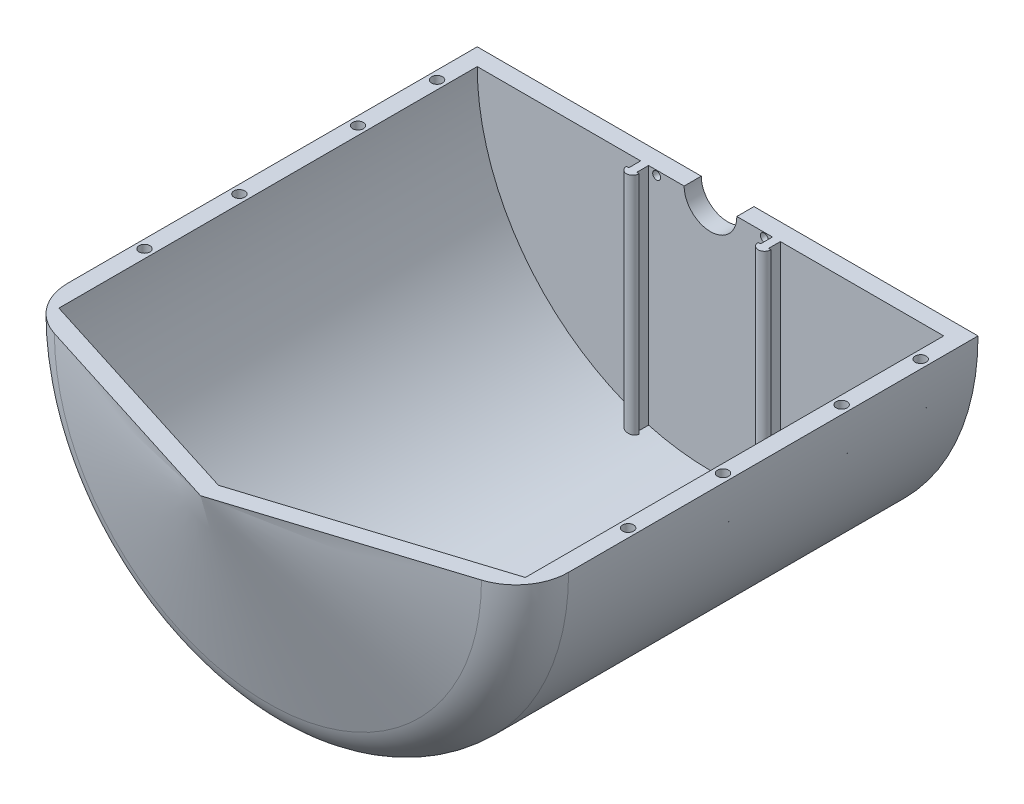
SolidWorks part; units mm, degrees
material "PVC 0.007 Plasticized"
ref_plane "Front Plane" through (0, 0, 0) normal (0, 0, 1) x (1, 0, 0)
ref_plane "Top Plane" through (0, 0, 0) normal (0, 1, 0) x (1, 0, 0)
ref_plane "Right Plane" through (0, 0, 0) normal (1, 0, 0) x (0, 0, -1)
sketch "Sketch1" plane through (0, 0, 0) normal (0, 1, 0) x (1, 0, 0)
  line L0 (0, 75) -> (95, 75)
  line L1 (95, 75) -> (95, -95)
  line L2 (95, -95) -> (0, -125)
  line L3 (0, -125) -> (0, 75) construction
  line L4 (0, 75) -> (0, -125)
  dimension "D1" = 200
  dimension "D2" = 170
  dimension "D3" = 95
  dimension "D4" = 75
  dimension "D5" = 95
revolve "Revolve1" add sketch "Sketch1" angle 180 about L3
sketch "Sketch2" plane through (0, 0, 0) normal (0, 1, 0) x (1, 0, 0)
  line L5 (0, 68.5) -> (0, -118.1836) construction
  line L6 (0, 68.5) -> (0, -118.1836)
  line L10 (-88.5, -90.2362) -> (0, -118.1836)
  line L11 (0, -118.1836) -> (88.5, -90.2362)
  line L12 (88.5, -90.2362) -> (88.5, 68.5)
  line L13 (88.5, 68.5) -> (-88.5, 68.5)
  line L14 (-88.5, 68.5) -> (-88.5, -90.2362)
  line L16 (0, -118.1836) -> (88.5, -90.2362)
  line L17 (88.5, -90.2362) -> (88.5, 68.5)
  line L18 (88.5, 68.5) -> (0, 68.5)
  dimension "D1" = 6.5
revolve "Cut-Revolve3" cut sketch "Sketch2" angle 360 about L5
sketch "Sketch3" plane through (0, 0, 0) normal (0, 1, 0) x (1, 0, 0)
  line L0 (-88.5, 68.5) -> (-95, 68.5) construction
  line L1 (-95, -95) -> (-95, 75) construction
  line L2 (-91.75, 68.5) -> (-91.75, -96.0263) construction
  line L3 (0, -125) -> (-95, -95) construction
  line L4 (0, 68.5) -> (0, -90.2362) construction
  line L5 (-88.5, 68.5) -> (88.5, 68.5) construction
  line L6 (88.5, -90.2362) -> (-88.5, -90.2362) construction
  circle A1 centre (-91.75, 56.5) radius 2.075
  circle A2 centre (-91.75, 26.5) radius 2.075
  circle A3 centre (-91.75, -18.5) radius 2.075
  circle A4 centre (-91.75, -54.5) radius 2.075
  circle A5 centre (91.75, -54.5) radius 2.075
  circle A6 centre (91.75, -18.5) radius 2.075
  circle A7 centre (91.75, 26.5) radius 2.075
  circle A8 centre (91.75, 56.5) radius 2.075
  dimension "D1" = 4.15
  dimension "D2" = 30
  dimension "D3" = 45
  dimension "D4" = 36
  dimension "D5" = 12
sketch "Sketch4" plane through (0, 0, 0) normal (0, 0, 1) x (1, 0, 0)
  line L1 (88.5, 0) -> (-88.5, 0)
  line L2 (88.5, 0) -> (-88.5, 0)
  line L6 (0, -88.5) -> (0, -52) construction
  line L7 (-76.787, -44) -> (76.787, -44)
  line L8 (-71.6118, -52) -> (71.6118, -52)
  arc A1 (-88.5, 0) -> (88.5, 0) centre (0, 0) ccw
  arc A2 (-88.5, 0) -> (88.5, 0) centre (0, 0) ccw
  dimension "D1" = 0
  dimension "D2" = 44.5
  dimension "D3" = 8
sketch "Sketch5" plane through (0, 0, 0) normal (0, 1, 0) x (1, 0, 0)
  line L1 (23.5, 64) -> (23.5, 68.5)
  line L4 (0, 0) -> (0, 89.957) construction
  line L8 (-27.4, 64) -> (-26.5, 64)
  line L9 (-26.5, 64) -> (-26.5, 68.5)
  line L10 (-22.6, 64) -> (-23.5, 64)
  line L11 (-23.5, 64) -> (-23.5, 68.5)
  line L12 (88.5, 68.5) -> (-88.5, 68.5) construction
  line L13 (-23.5, 68.5) -> (-26.5, 68.5)
  line L14 (22.6, 64) -> (23.5, 64)
  line L15 (27.4, 64) -> (26.5, 64)
  line L16 (26.5, 64) -> (26.5, 68.5)
  line L17 (23.5, 68.5) -> (26.5, 68.5)
  arc A0 (-27.4, 64) -> (-22.6, 64) centre (-25, 64) ccw
  arc A2 (27.4, 64) -> (22.6, 64) centre (25, 64) cw
  dimension "D2" = 2.4
  dimension "D5" = 3
  dimension "D1" = 4.5
  dimension "D3" = 25
extrude "Boss-Extrude8" add sketch "Sketch5" against normal up to surface (85.5657 mm away)
extrude "Boss-Extrude10" [suppressed] add sketch "Sketch4" along normal mid plane 120 contours L7 A2 L8
sketch "Sketch7" plane through (0, 0, -68.5) normal (0, 0, 1) x (1, 0, 0)
  line L0 (0, 0) -> (20.4252, -1.75) construction
  line L2 (0, 21.148) -> (0, -18.5427) construction
  line L3 (0, 0) -> (95, 0) construction
  circle A0 centre (0, 0) radius 10
  circle A1 centre (20.4252, -1.75) radius 1.5
  circle A2 centre (-20.4252, -1.75) radius 1.5
  dimension "D1" = 20
  dimension "D2" = 3
  dimension "D4" = 1.75
  dimension "D3" = 20.5
extrude "Cut-Extrude1" cut sketch "Sketch7" against normal blind 10
sketch "Sketch8" plane through (0, 0, 0) normal (0, 0, 1) x (1, 0, 0)
  line L0 (0, 0) -> (0, -30) construction
  line L1 (0, -30) -> (90.1388, -30) construction
  line L2 (90.1388, -30) -> (-90.1388, -30) construction
  line L3 (90.1388, -30) -> (130.1388, -30)
  line L4 (130.1388, -30) -> (92.2971, -22.5)
  line L5 (92.2971, -22.5) -> (90.1388, -30)
  line L6 (-130.1388, -30) -> (-92.2971, -22.5)
  line L7 (-90.1388, -30) -> (-130.1388, -30)
  line L8 (-92.2971, -22.5) -> (-90.1388, -30)
  arc A0 (-95, 0) -> (95, 0) centre (0, 0) ccw construction
  dimension "D1" = 40
  dimension "D2" = 7.5
  dimension "D3" = 30
extrude "Boss-Extrude11" [suppressed] add sketch "Sketch8" along normal mid plane 50
extrude "Cut-Extrude3" cut sketch "Sketch3" against normal blind 15
fillet "Fillet1" radius 20 1 edges at (0, -95, 95)
